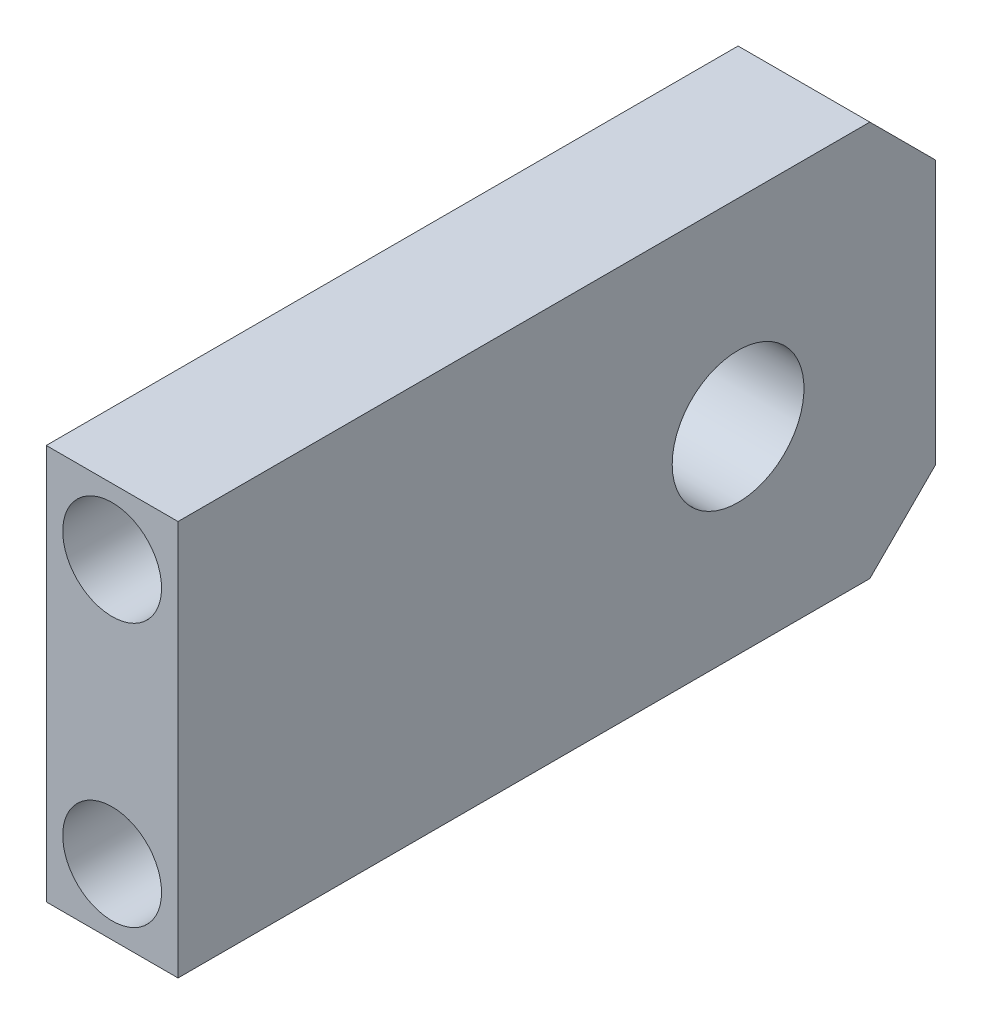
SolidWorks part; units mm, degrees
ref_plane "Front Plane" through (0, 0, 0) normal (0, 0, 1) x (1, 0, 0)
ref_plane "Top Plane" through (0, 0, 0) normal (0, 1, 0) x (1, 0, 0)
ref_plane "Right Plane" through (0, 0, 0) normal (1, 0, 0) x (0, 0, -1)
sketch "Sketch3" plane through (0, 0, 0) normal (1, 0, 0) x (0, 0, -1)
  line L1 (0, 0) -> (23, 0)
  line L2 (0, 0) -> (0, -12)
  line L3 (0, -12) -> (23, -12)
  line L4 (23, 0) -> (23, -12)
  dimension "D1" = 23
  dimension "D2" = 12
extrude "Boss-Extrude1" add sketch "Sketch3" along normal blind 4 contours L1 L4 L3 L2
sketch "Sketch7" plane through (0, 0, 0) normal (0, 0, 1) x (1, 0, 0)
  line L0 (0, -12) -> (4, -12) construction
  line L1 (2, -12) -> (2, 0) construction
  line L2 (4, 0) -> (0, 0) construction
  circle A0 centre (2, -2) radius 1.5
  circle A1 centre (2, -10) radius 1.5
  dimension "D3" = 3
  dimension "D4" = 3
  dimension "D1" = 2
  dimension "D2" = 2
extrude "Cut-Extrude1" cut sketch "Sketch7" against normal blind 10
sketch "Sketch8" plane through (0, 0, 0) normal (-1, 0, 0) x (0, 0, 1)
  line L0 (-23, 0) -> (-23, -12) construction
  line L1 (0, -12) -> (-23, -12) construction
  line L2 (-23, 0) -> (-23, -12) construction
  line L3 (-23, -12) -> (-23, -6) construction
  line L4 (-23, -6) -> (0, -6) construction
  line L5 (0, 0) -> (0, -12) construction
  circle A0 centre (-17, -6) radius 2
  dimension "D2" = 4
  dimension "D1" = 17
extrude "Cut-Extrude2" cut sketch "Sketch8" against normal through all
chamfer "Chamfer1" distance 2 angle 45 2 edges at (2, -12, -23) (2, 0, -23)
